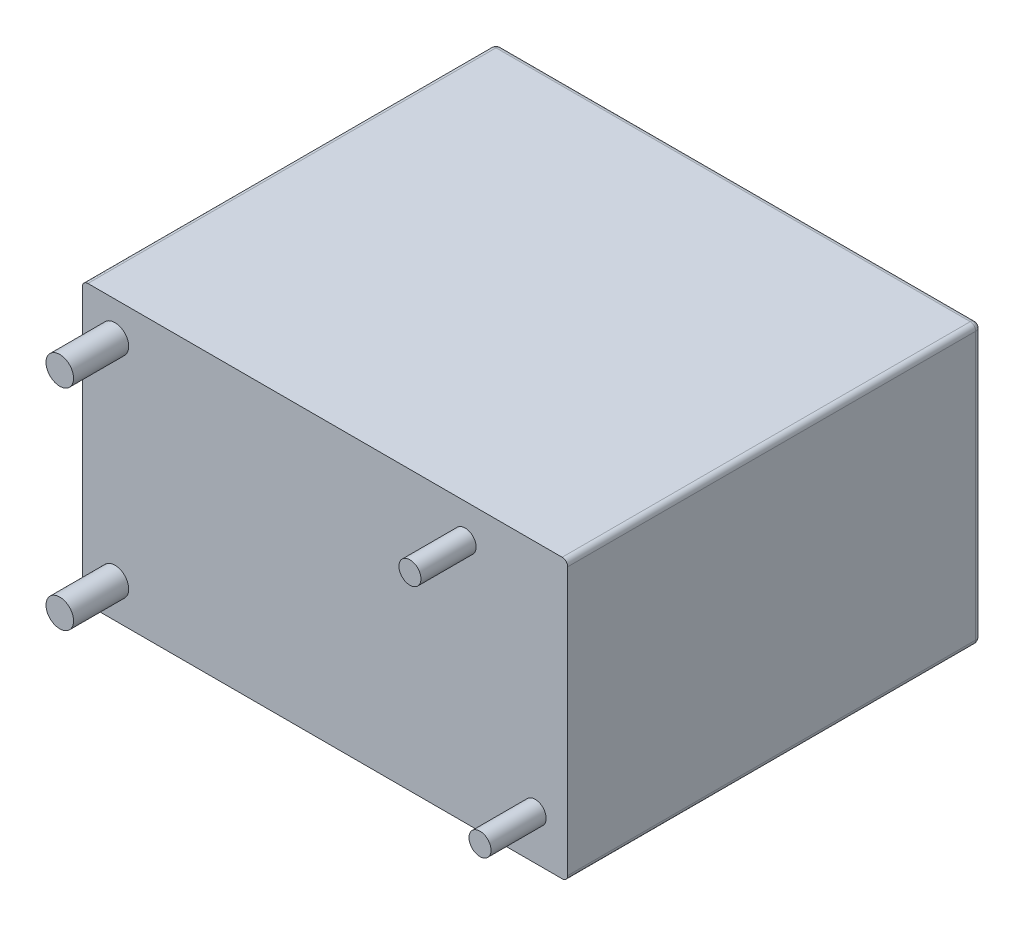
SolidWorks part; units mm, degrees
ref_plane "前视基准面" through (0, 0, 0) normal (0, 0, 1) x (1, 0, 0)
ref_plane "上视基准面" through (0, 0, 0) normal (0, 1, 0) x (1, 0, 0)
ref_plane "右视基准面" through (0, 0, 0) normal (1, 0, 0) x (0, 0, -1)
sketch "草图1" plane through (0, 0, 0) normal (0, 0, 1) x (1, 0, 0)
  line L1 (0, 0) -> (17.6, 0)
  line L2 (0, 0) -> (0, 10.1)
  line L3 (0, 10.1) -> (17.6, 10.1)
  line L4 (17.6, 0) -> (17.6, 10.1)
  dimension "D1" = 10.1
  dimension "D2" = 17.6
extrude "凸台-拉伸1" add sketch "草图1" against normal blind 15
sketch "草图2" plane through (0, 0, 0) normal (0, 0, 1) x (1, 0, 0)
  line L0 (0, 5.05) -> (17.6, 5.05) construction
  line L1 (0, 10.1) -> (0, 0) construction
  line L2 (17.6, 0) -> (17.6, 10.1) construction
  line L3 (8.8, 10.1) -> (8.8, 0) construction
  line L4 (17.6, 10.1) -> (0, 10.1) construction
  line L5 (0, 0) -> (17.6, 0) construction
  circle A0 centre (1.18, 8.86) radius 0.5
  circle A1 centre (13.88, 8.86) radius 0.4
  circle A2 centre (12.38, 1.607) radius 0.4 construction
  circle A3 centre (16.42, 1.607) radius 0.4
  circle A4 centre (1.18, 1.24) radius 0.5
  dimension "D1" = 1
  dimension "D2" = 7.62
  dimension "D3" = 12.7
  dimension "D4" = 1.5
  dimension "D5" = 2.54
  dimension "D6" = 0.8
  dimension "D7" = 0.8
  dimension "D8" = 0.8
  dimension "D9" = 1.18
extrude "凸台-拉伸2" add sketch "草图2" along normal blind 2
fillet "圆角1" radius 0.2 8 edges at (17.6, 0, -7.5) (0, 0, -7.5) (8.8, 0, -15) (17.6, 5.05, -15) (0, 5.05, -15) (0, 10.1, -7.5) (17.6, 10.1, -7.5) (8.8, 10.1, -15)
sketch "草图3" plane through (0, 0, -15) normal (0, 0, -1) x (-1, 0, 0)
  circle A1 centre (-15.9103, 8.7934) radius 0.5
  dimension "D2" = 1
extrude "切除-拉伸1" cut sketch "草图3" against normal blind 0.5
